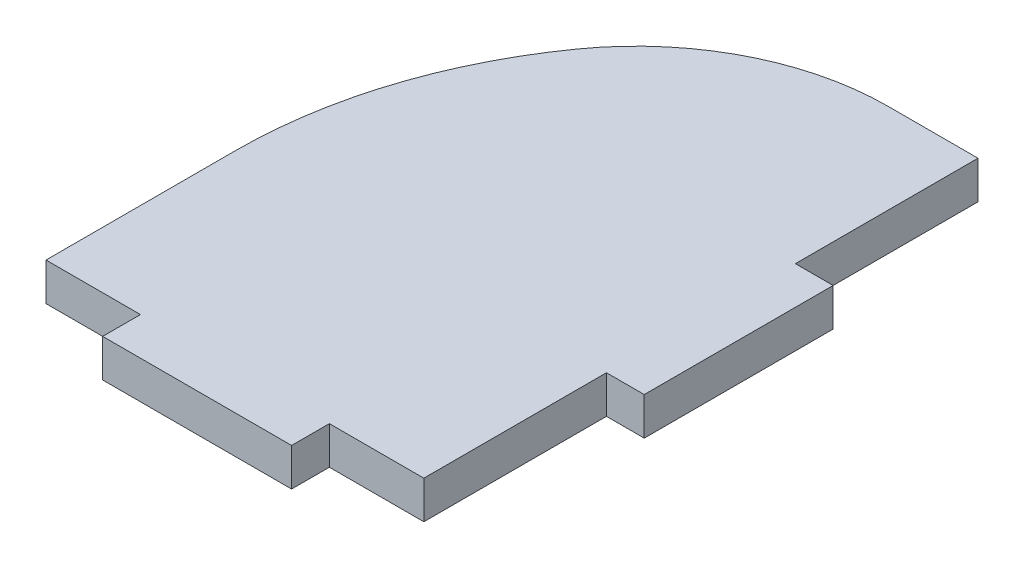
SolidWorks part; units mm, degrees
ref_plane "Front" through (0, 0, 0) normal (0, 0, 1) x (1, 0, 0)
ref_plane "Top" through (0, 0, 0) normal (0, 1, 0) x (1, 0, 0)
ref_plane "Right" through (0, 0, 0) normal (1, 0, 0) x (0, 0, -1)
sketch "Sketch1" plane through (0, 0, 0) normal (0, 1, 0) x (1, 0, 0)
  line L1 (-15, 22) -> (15, 22)
  line L2 (-15, 22) -> (-15, -22)
  line L3 (-15, -22) -> (15, -22)
  line L4 (15, 22) -> (15, -22)
  line L5 (-15, 22) -> (15, -22) construction
  line L6 (-15, -22) -> (15, 22) construction
  point P0 (0, 0)
  dimension "D1" = 44
  dimension "D2" = 30
extrude "Boss-Extrude1" add sketch "Sketch1" along normal blind 3
sketch "Sketch2" plane through (0, 3, 0) normal (0, 1, 0) x (1, 0, 0)
  line L0 (15, 22) -> (-15, 22) construction
  line L1 (15, -22) -> (15, 22) construction
  line L4 (-15, -7) -> (-15, 22)
  line L5 (-15, 22) -> (0, 22)
  line L7 (-15, -22) -> (15, -22) construction
  line L9 (-15, 22) -> (-15, -22) construction
  arc A0 (-15, -7) -> (0, 22) centre (20.5333, -7) cw
  dimension "D1" = 15
  dimension "D2" = 15
extrude "Cut-Extrude1" cut sketch "Sketch2" against normal through all
sketch "Sketch3" plane through (0, 3, 0) normal (0, 1, 0) x (1, 0, 0)
  line L0 (-15, -22) -> (15, -22) construction
  line L1 (7.5, -22) -> (-7.5, -22)
  line L2 (7.5, -22) -> (7.5, -25)
  line L3 (7.5, -25) -> (-7.5, -25)
  line L4 (-7.5, -22) -> (-7.5, -25)
  line L5 (15, -22) -> (15, 22) construction
  line L6 (15, -7.5) -> (18, -7.5)
  line L7 (15, -7.5) -> (15, 7.5)
  line L8 (15, 7.5) -> (18, 7.5)
  line L9 (18, -7.5) -> (18, 7.5)
  line L10 (0, -22) -> (0, 0) construction
  line L11 (0, 0) -> (15, 0) construction
  dimension "D1" = 3
  dimension "D2" = 15
extrude "Boss-Extrude2" add sketch "Sketch3" against normal blind 3
fillet "Fillet1" radius 20 1 edges at (0, 1.5, -22)
